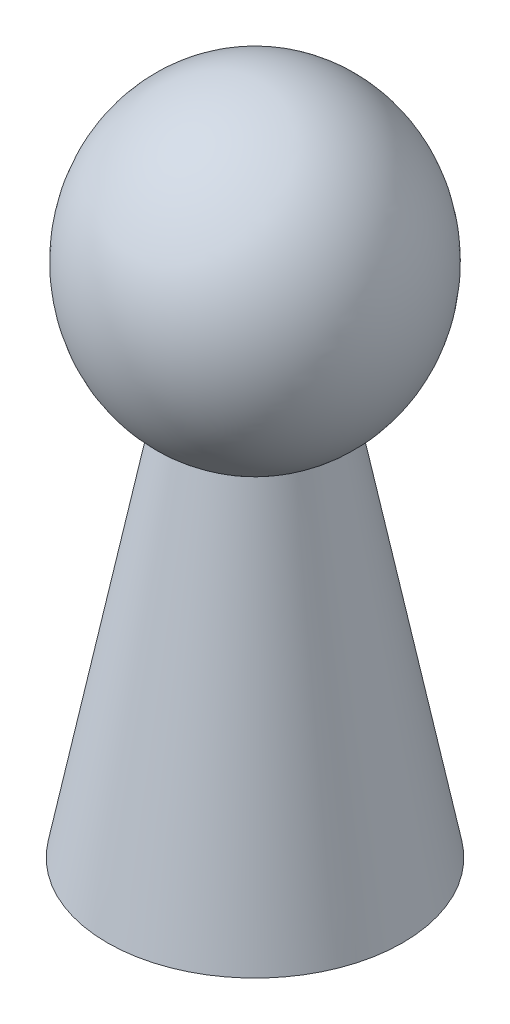
SolidWorks part; units mm, degrees
ref_plane "Plan de face" through (0, 0, 0) normal (0, 0, 1) x (1, 0, 0)
ref_plane "Plan de dessus" through (0, 0, 0) normal (0, 1, 0) x (1, 0, 0)
ref_plane "Plan de droite" through (0, 0, 0) normal (1, 0, 0) x (0, 0, -1)
sketch "Esquisse1" plane through (0, 0, 0) normal (0, 0, 1) x (1, 0, 0)
  line L0 (0, 6.8425) -> (0, -6.6121) construction
  line L1 (0, 0) -> (8.9, 0)
  line L2 (8.9, 0) -> (4.4, 23)
  line L3 (0, 0) -> (0, 40.5)
  ellipse E0 centre (0, 31.1134) end of major axis (0, 21.7269) minor radius 8.75 (4.4, 23) -> (0, 40.5) ccw
  point P8 (0, 0)
  point P14 (0, 30.1331)
  point P15 (0, 17.9065)
  point P16 (0, 29.3527)
  point P17 (0, 0)
  point P18 (0, 0)
  point P19 (8.7319, 24.6051)
  point P20 (0, 14.164)
  point P21 (0, 50.7707)
  dimension "D1" = 17.5
  dimension "D2" = 17.5
  dimension "D3" = 8.9
  dimension "D4" = 23
  dimension "D5" = 4.4
revolve "Révolution1" add sketch "Esquisse1" angle 360 about L0
